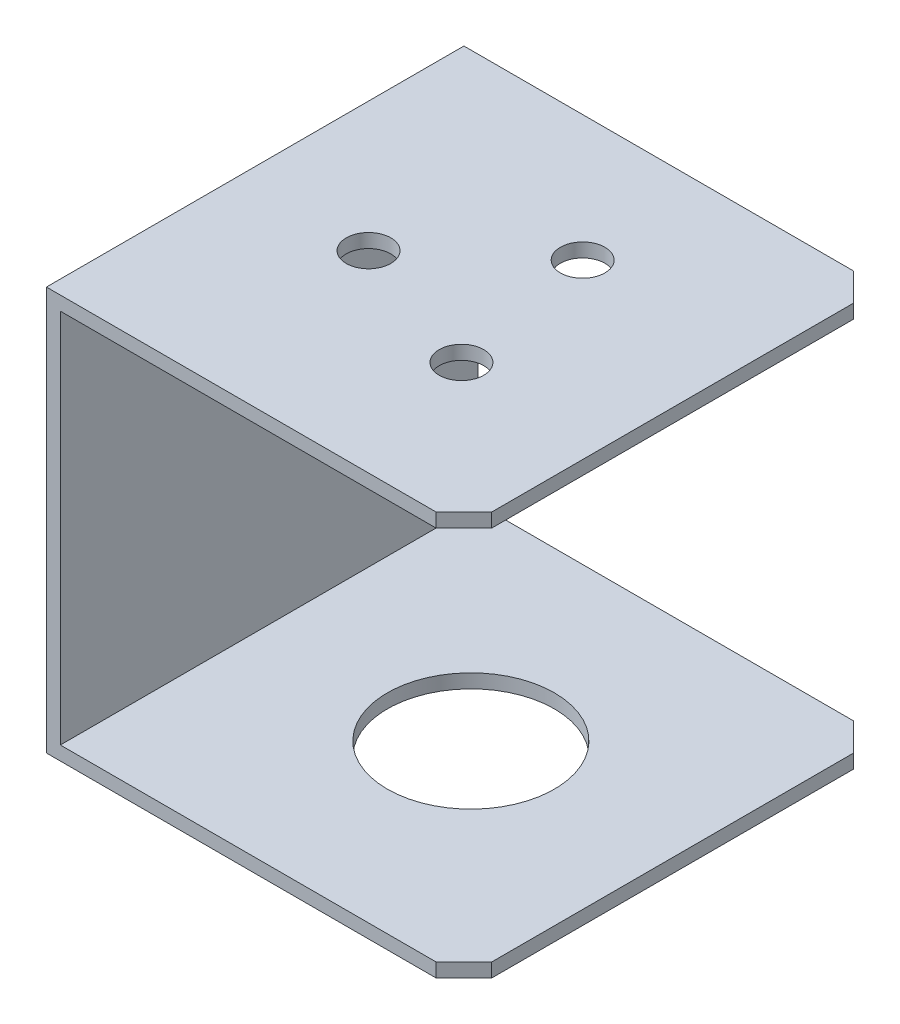
SolidWorks part; units mm, degrees
ref_plane "Front Plane" through (0, 0, 0) normal (0, 0, 1) x (1, 0, 0)
ref_plane "Top Plane" through (0, 0, 0) normal (0, 1, 0) x (1, 0, 0)
ref_plane "Right Plane" through (0, 0, 0) normal (1, 0, 0) x (0, 0, -1)
sketch "Sketch1" plane through (0, 0, 0) normal (0, 0, 1) x (1, 0, 0)
  line L1 (0, 0) -> (30, 0)
  line L2 (0, 0) -> (0, 1)
  line L3 (1, 1) -> (30, 1)
  line L4 (30, 0) -> (30, 1)
  line L6 (0, 1) -> (0, 28)
  line L8 (1, 1) -> (1, 28)
  line L9 (1, 28) -> (30, 28)
  line L10 (0, 28) -> (0, 29)
  line L11 (0, 29) -> (30, 29)
  line L12 (30, 28) -> (30, 29)
extrude "Boss-Extrude1" add sketch "Sketch1" along normal blind 30
sketch "Sketch2" plane through (0, 1, 0) normal (0, 1, 0) x (1, 0, 0)
  line L0 (30, -30) -> (30, 0) construction
  line L1 (30, -30) -> (0, -30) construction
  circle A0 centre (15.5, -15) radius 6
  dimension "D1" = 14.5
  dimension "D2" = 15
sketch "Sketch3" plane through (0, 29, 0) normal (0, 1, 0) x (1, 0, 0)
  circle A0 centre (19.6032, -19.7805) radius 1.6
  circle A3 centre (9.3083, -16.1632) radius 1.6
  circle A5 centre (17.5884, -9.0562) radius 1.6
  point P16 (15.5, -15)
  dimension "D2" = 3
extrude "Cut-Extrude1" cut sketch "Sketch3" against normal blind 10
extrude "Cut-Extrude2" cut sketch "Sketch2" against normal blind 10
chamfer "Chamfer1" distance 2 angle 45 4 edges at (30, 0.5, 0) (30, 28.5, 30) (30, 0.5, 30) (30, 28.5, 0)
